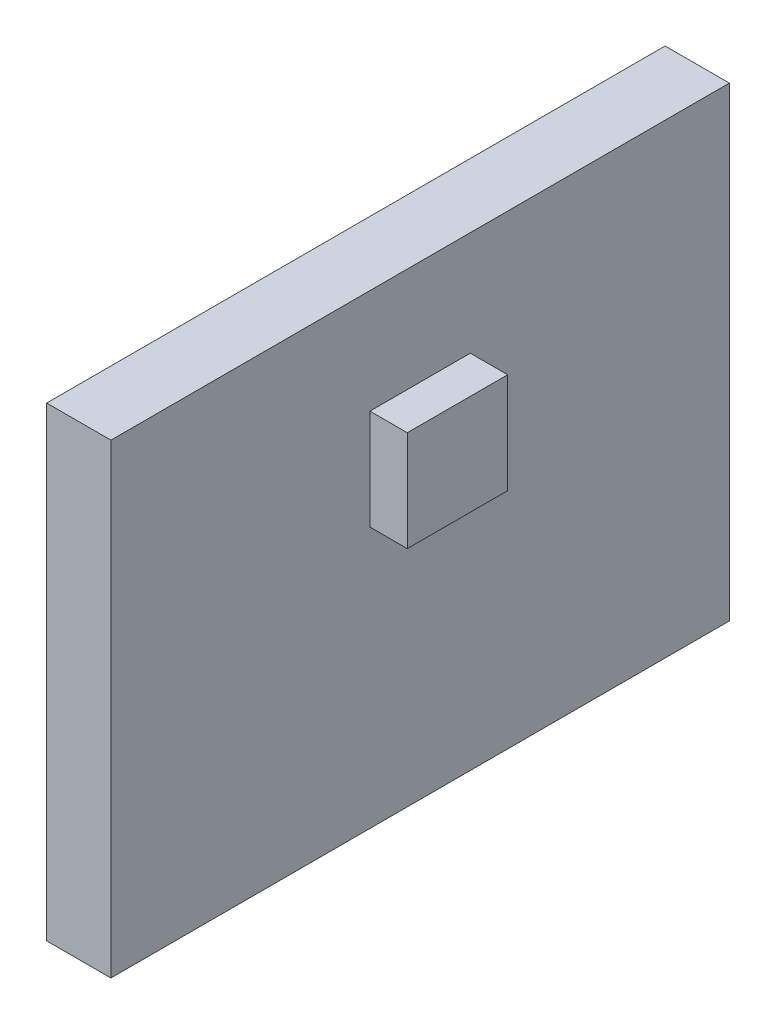
SolidWorks part; units mm, degrees
ref_plane "Front Plane" through (0, 0, 0) normal (0, 0, 1) x (1, 0, 0)
ref_plane "Top Plane" through (0, 0, 0) normal (0, 1, 0) x (1, 0, 0)
ref_plane "Right Plane" through (0, 0, 0) normal (1, 0, 0) x (0, 0, -1)
ref_plane "Plane1" through (0, 0, 18.3) normal (0, 0, 1) x (1, 0, 0)
sketch "Sketch1" plane through (0, 0, 18.3) normal (0, 0, 1) x (1, 0, 0)
  line L1 (-44.8, -132.5) -> (-43.2, -132.5)
  line L2 (-44.8, -132.5) -> (-44.8, -120.9)
  line L3 (-44.8, -120.9) -> (-43.2, -120.9)
  line L4 (-43.2, -132.5) -> (-43.2, -120.9)
  line L5 (-44.8, -132.5) -> (-43.2, -120.9) construction
  line L6 (-44.8, -120.9) -> (-43.2, -132.5) construction
  point P0 (-44, -126.7)
extrude "Boss-Extrude1" add sketch "Sketch1" along normal blind 15.4
ref_plane "Plane2" through (0, 0, 24.75) normal (0, 0, 1) x (1, 0, 0)
sketch "Sketch2" plane through (0, 0, 24.75) normal (0, 0, 1) x (1, 0, 0)
  line L1 (-43.2, -126) -> (-42.27, -126)
  line L2 (-43.2, -126) -> (-43.2, -123.5)
  line L3 (-43.2, -123.5) -> (-42.27, -123.5)
  line L4 (-42.27, -126) -> (-42.27, -123.5)
  line L5 (-43.2, -126) -> (-42.27, -123.5) construction
  line L6 (-43.2, -123.5) -> (-42.27, -126) construction
  point P0 (-42.735, -124.75)
extrude "Boss-Extrude2" add sketch "Sketch2" along normal blind 2.5
